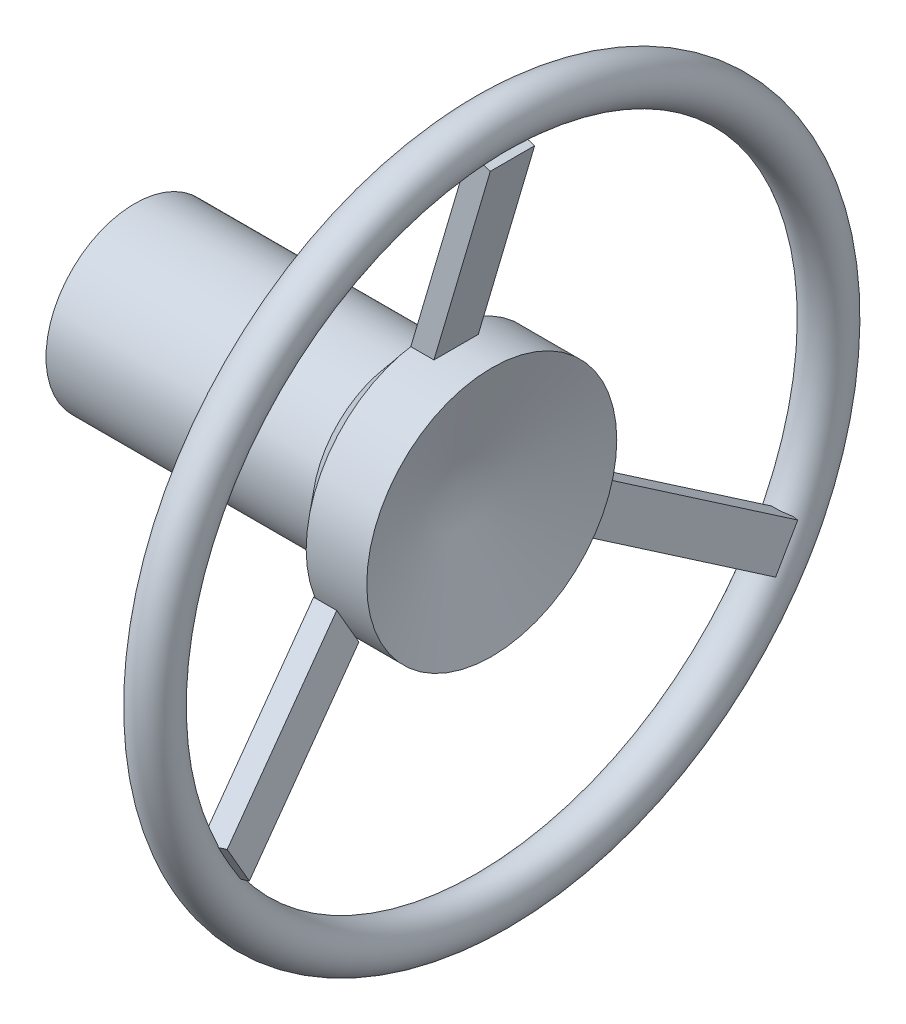
SolidWorks part; units mm, degrees
ref_plane "Front Plane" through (0, 0, 0) normal (0, 0, 1) x (1, 0, 0)
ref_plane "Top Plane" through (0, 0, 0) normal (0, 1, 0) x (1, 0, 0)
ref_plane "Right Plane" through (0, 0, 0) normal (1, 0, 0) x (0, 0, -1)
sketch "Sketch1" plane through (0, 0, 0) normal (0, 0, 1) x (1, 0, 0)
  line L0 (-6, 0) -> (0, 0)
  line L1 (0, 0) -> (0.6875, 0.8194)
  line L2 (0.6875, 0.8194) -> (2.0539, 0.8194)
  line L3 (2.0539, 0.8194) -> (1.1536, -2)
  line L4 (1.1536, -2) -> (-6, -2)
  line L5 (-6, -2) -> (-6, 0)
  dimension "D1" = 6
  dimension "D2" = 2
  dimension "D5" = 130
revolve "Revolve1" add sketch "Sketch1" angle 360 about L4
sketch "Sketch2" plane through (-6, 0, 0) normal (-1, 0, 0) x (0, 0, 1)
  circle A0 centre (0, -2) radius 1.5
  dimension "D1" = 3
extrude "Cut-Extrude1" cut sketch "Sketch2" against normal blind 6
sketch "Sketch3" plane through (0, 0, 0) normal (0, 0, 1) x (1, 0, 0)
  line L0 (-6, 0) -> (-6, -4) construction
  line L1 (-6, -2) -> (-6.9928, -2) construction
  circle A0 centre (2.0539, 5.5961) radius 0.5
  point P4 (-6, -2)
  dimension "D1" = 1
revolve "Revolve2" add sketch "Sketch3" angle 360 about L1
sketch "Sketch4" plane through (0, 0, 0) normal (0, 0, 1) x (1, 0, 0)
  line L0 (1.2493, 0.8194) -> (2.521, 5.1408)
  line L1 (2.0539, 0.8194) -> (0.6875, 0.8194) construction
  line L2 (0.7281, 0.8194) -> (2.0414, 5.282)
  line L3 (2.0414, 5.282) -> (2.521, 5.1408)
  line L4 (1.2493, 0.8194) -> (0.7281, 0.8194)
  line L5 (0.7696, 0.9605) -> (2.0414, 5.282) construction
  dimension "D1" = 0.5
extrude "Boss-Extrude1" add sketch "Sketch4" along normal mid plane 1
pattern_circular "CirPattern1" count 3 over 360 about axis through (0, -2, 0) along (1, 0, 0) of "Boss-Extrude1"
